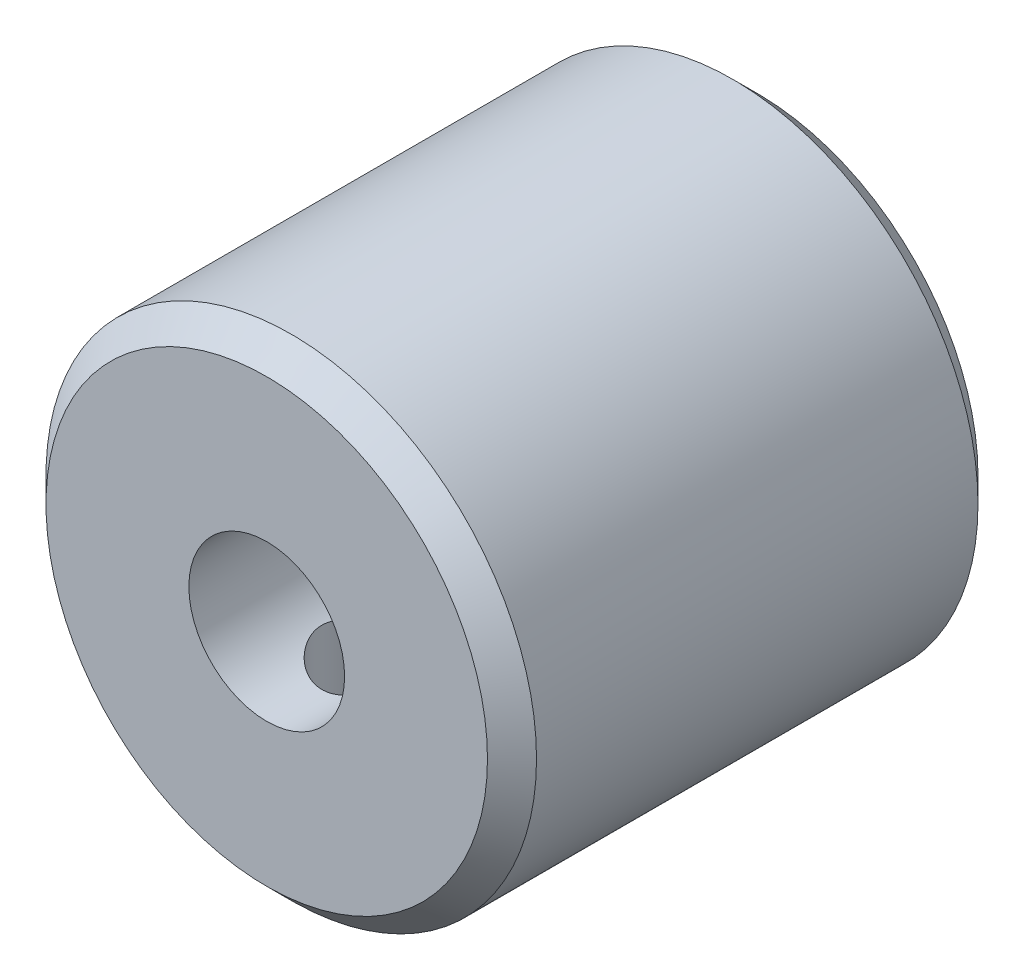
SolidWorks part; units mm, degrees
ref_plane "Front Plane" through (0, 0, 0) normal (0, 0, 1) x (1, 0, 0)
ref_plane "Top Plane" through (0, 0, 0) normal (0, 1, 0) x (1, 0, 0)
ref_plane "Right Plane" through (0, 0, 0) normal (1, 0, 0) x (0, 0, -1)
sketch "Sketch1" plane through (0, 0, 0) normal (0, 0, 1) x (1, 0, 0)
  circle A0 centre (0, 0) radius 5
  circle A1 centre (0, 0) radius 1.5875
  dimension "D1" = 10
  dimension "D2" = 3.175
extrude "Boss-Extrude1" add sketch "Sketch1" along normal mid plane 10 contours A0
sketch "Sketch2" plane through (0, 0, -5) normal (0, 0, -1) x (-1, 0, 0)
  circle A0 centre (0, 0) radius 3.1
  dimension "D1" = 6.2
extrude "Cut-Extrude1" cut sketch "Sketch2" against normal blind 5
chamfer "Chamfer1" distance 0.5 angle 45 2 edges at (5, 0, -5) (5, 0, 5)
sketch "Sketch3" plane through (0, 0, 0) normal (0, 1, 0) x (1, 0, 0)
  line L0 (0, -3) -> (0, 3) construction
  point P2 (0, 0)
  point P3 (0, 0)
  point P4 (0, 0)
  dimension "D1" = 6
ref_plane "Plane1" through (0, -5, 0) normal (0, -1, 0) x (-1, 0, 0)
hole_wizard "M2.2x0.45 Tapped Hole1" positions "Sketch4" profile "Sketch5" tap size "M2.2x0.45" standard "ANSI Metric"
sketch "Sketch4" plane through (0, -5, 0) normal (0, -1, 0) x (-1, 0, 0)
  point P0 (0, -3)
  point P2 (0, 3)
  point P5 (0, 0)
  point P7 (0, 0)
sketch "Sketch5" plane through (0, -5, 3) normal (1, 0, 0) x (0, 0, -1)
  line L0 (0, 0) -> (0, 3.4125)
  line L1 (0, 3.4125) -> (0.875, 3.4125)
  line L2 (0.875, 3.4125) -> (0.875, 0)
  line L5 (0.875, 0) -> (0, 0)
  line L11 (0, -6.35) -> (0, 107.95) construction
  dimension "Thru Tap Drill Dia." = 1.75
  dimension "Thru Tap Drill Depth" = 3.4125
cosmetic thread "Hole Thread1"
cosmetic thread "Hole Thread2"
